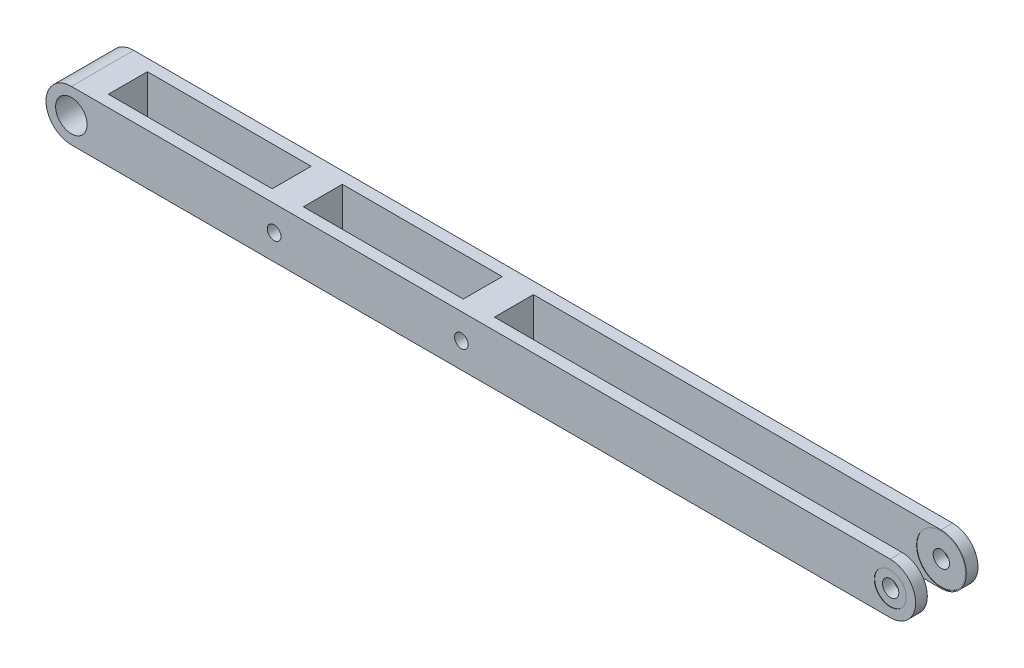
SolidWorks part; units mm, degrees
ref_plane "前视基准面" through (0, 0, 0) normal (0, 0, 1) x (1, 0, 0)
ref_plane "上视基准面" through (0, 0, 0) normal (0, 1, 0) x (1, 0, 0)
ref_plane "右视基准面" through (0, 0, 0) normal (1, 0, 0) x (0, 0, -1)
sketch "草图1" plane through (0, 0, 0) normal (0, 0, 1) x (1, 0, 0)
  line L0 (0, 0) -> (21.75, 0) construction
  line L1 (0, 6.5) -> (210, 6.5)
  line L2 (0, -6.5) -> (210, -6.5)
  line L3 (21.75, 0) -> (210, 0) construction
  arc A0 (0, 6.5) -> (0, -6.5) centre (0, 0) ccw
  arc A1 (210, -6.5) -> (210, 6.5) centre (210, 0) ccw
  circle A2 centre (0, 0) radius 4.04
  circle A3 centre (100, 0) radius 1.75
  circle A4 centre (210, 0) radius 2.1
  circle A10 centre (52, 0) radius 1.75
  point P3 (100, 0)
  dimension "D2" = 13
  dimension "D3" = 8.08
  dimension "D4" = 3.5
  dimension "D5" = 4.2
  dimension "D6" = 6.5
  dimension "D1" = 210
extrude "凸台-拉伸1" add sketch "草图1" against normal blind 16
sketch "草图2" plane through (0, -6.5, 0) normal (0, -1, 0) x (1, 0, 0)
  line L0 (148.5, -3) -> (153.5, -3)
  line L1 (148.5, -13) -> (153.5, -13)
  line L4 (0, 0) -> (0, -16) construction
  line L6 (6.5, -3) -> (6.5, -13)
  line L7 (0, 0) -> (210, 0) construction
  line L8 (0, -16) -> (210, -16) construction
  line L9 (6.5, -3) -> (48.5, -3)
  line L10 (216.5, -16) -> (216.5, 0) construction
  line L11 (216.5, -3) -> (216.5, -13)
  line L12 (216.5, -13) -> (153.5, -13)
  line L13 (48.5, -3) -> (48.5, -13)
  line L14 (56.5, -3) -> (56.5, -13)
  line L15 (97.5, -3) -> (97.5, -13)
  line L16 (105.5, -3) -> (105.5, -13)
  line L19 (56.5, -3) -> (97.5, -3)
  line L20 (48.5, -13) -> (6.5, -13)
  line L21 (97.5, -13) -> (56.5, -13)
  line L22 (105.5, -3) -> (148.5, -3)
  line L23 (148.5, -13) -> (105.5, -13)
  line L24 (153.5, -3) -> (216.5, -3)
  dimension "D1" = 6.5
  dimension "D2" = 3
  dimension "D3" = 3
  dimension "D6" = 8
  dimension "D7" = 8
  dimension "D8" = 42
  dimension "D9" = 41
extrude "切除-拉伸1" cut sketch "草图2" against normal through all
sketch "草图3" plane through (0, 0, 0) normal (0, 0, 1) x (1, 0, 0)
  circle A0 centre (210, 0) radius 4.1
extrude "下轴_外侧A_让位0p1" cut sketch "草图3" against normal blind 0.1
sketch "草图4" plane through (0, 0, -16) normal (0, 0, -1) x (-1, 0, 0)
  circle A0 centre (-210, 0) radius 4.1
extrude "下轴_外侧B_让位0p1" cut sketch "草图4" against normal blind 0.1
sketch "草图5" plane through (0, 0, -3) normal (0, 0, -1) x (-1, 0, 0)
  circle A0 centre (-210, 0) radius 6.25
extrude "下轴_内侧A_让位0p1" cut sketch "草图5" against normal blind 0.1
sketch "草图6" plane through (0, 0, -13) normal (0, 0, 1) x (1, 0, 0)
  circle A0 centre (210, 0) radius 6.25
extrude "下轴_内侧B_让位0p1" cut sketch "草图6" against normal blind 0.1
